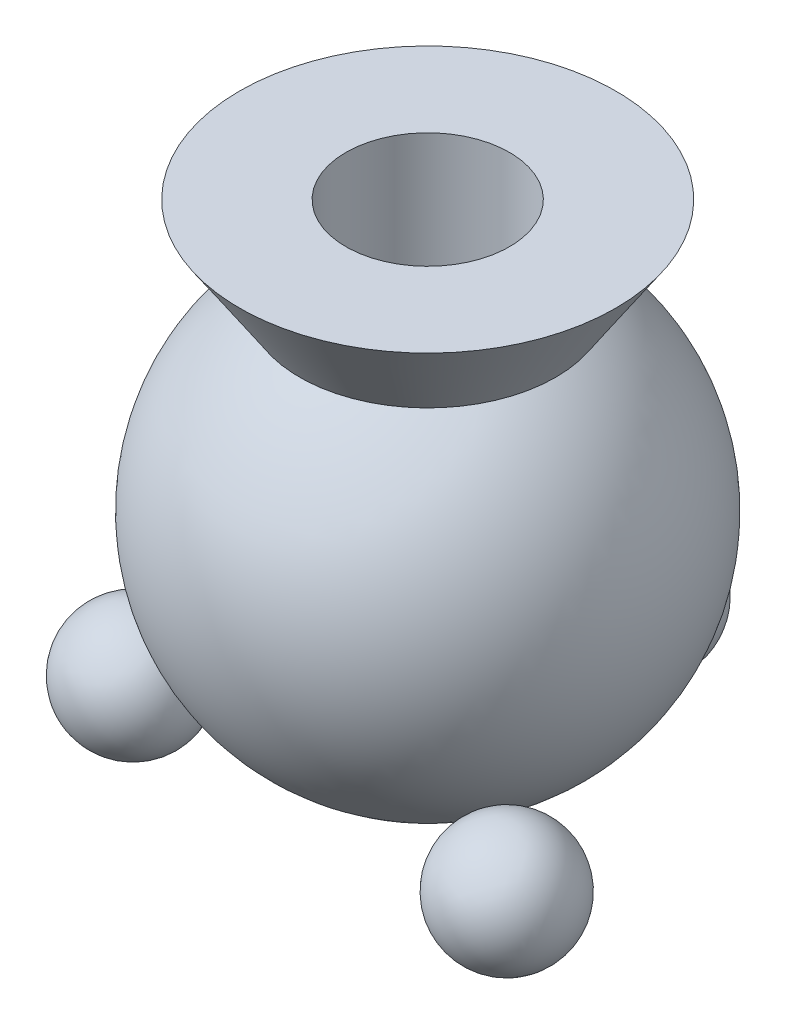
SolidWorks part; units mm, degrees
ref_plane "Front Plane" through (0, 0, 0) normal (0, 0, 1) x (1, 0, 0)
ref_plane "Top Plane" through (0, 0, 0) normal (0, 1, 0) x (1, 0, 0)
ref_plane "Right Plane" through (0, 0, 0) normal (1, 0, 0) x (0, 0, -1)
sketch "Sketch1" plane through (0, 0, 0) normal (0, 0, 1) x (1, 0, 0)
  line L0 (0, 35) -> (0, 0)
  line L1 (0, 0) -> (-50.1775, 0) construction
  line L2 (10, 60) -> (23, 60)
  line L3 (23, 60) -> (15.6525, 49)
  line L7 (0, 35) -> (10, 35)
  line L8 (10, 60) -> (10, 35)
  arc A0 (0, 0) -> (15.6525, 49) centre (0, 27) ccw
  dimension "D4" = 27
  dimension "D3" = 11
  dimension "D5" = 10
  dimension "D6" = 25
revolve "Revolve1" add sketch "Sketch1" angle 360 about L0
sketch "Sketch4" plane through (0, 0, 0) normal (1, 0, 0) x (0, 0, -1)
  line L0 (0.7599, 26.3597) -> (32.1185, -0.0629) construction
  line L1 (20.6476, 9.6024) -> (32.1185, -0.0629)
  arc A0 (32.1185, -0.0629) -> (20.6476, 9.6024) centre (26.3831, 4.7697) ccw
  arc A1 (-15.6525, 49) -> (15.6525, 49) centre (0, 27) ccw construction
  dimension "D1" = 15
revolve "Revolve5" add sketch "Sketch4" angle 360 about L0
pattern_circular "CirPattern2" count 3 over 360 about axis through (0, 0, 0) along (0, 1, 0) of bodies 105
